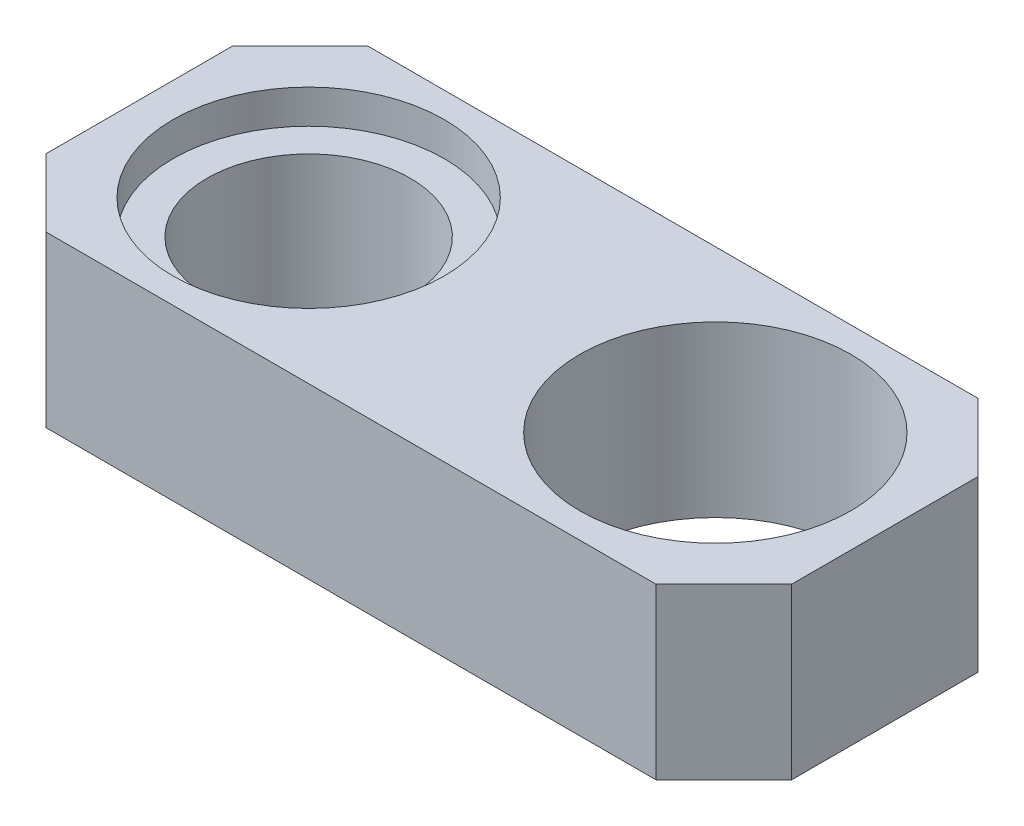
SolidWorks part; units mm, degrees
ref_plane "前视基准面" through (0, 0, 0) normal (0, 0, 1) x (1, 0, 0)
ref_plane "上视基准面" through (0, 0, 0) normal (0, 1, 0) x (1, 0, 0)
ref_plane "右视基准面" through (0, 0, 0) normal (1, 0, 0) x (0, 0, -1)
sketch "草图1" plane through (0, 0, 0) normal (0, 1, 0) x (1, 0, 0)
  line L1 (11, -4.75) -> (-11, -4.75)
  line L2 (11, -4.75) -> (11, 4.75)
  line L3 (11, 4.75) -> (-11, 4.75)
  line L4 (-11, -4.75) -> (-11, 4.75)
  line L5 (11, -4.75) -> (-11, 4.75) construction
  line L6 (11, 4.75) -> (-11, -4.75) construction
  point P0 (0, 0)
  dimension "D1" = 9.5
  dimension "D2" = 22
extrude "凸台-拉伸1" add sketch "草图1" along normal mid plane 5
sketch "草图2" plane through (0, 2.5, 0) normal (0, 1, 0) x (1, 0, 0)
  line L0 (0, 0) -> (0, 50000) construction
  line L1 (11, 4.75) -> (-11, 4.75) construction
  circle A0 centre (6, 0) radius 4
  point P5 (0, 4.75)
  dimension "D1" = 12
  dimension "D2" = 8
extrude "切除-拉伸1" cut sketch "草图2" against normal through all
sketch "草图3" plane through (0, 2.5, 0) normal (0, 1, 0) x (1, 0, 0)
  circle A0 centre (-6, 0) radius 4
  dimension "D1" = 8
  dimension "D2" = 6
extrude "切除-拉伸2" cut sketch "草图3" against normal blind 1
sketch "草图4" plane through (0, 1.5, 0) normal (0, 1, 0) x (1, 0, 0)
  circle A0 centre (-6, 0) radius 3
  circle A1 centre (-6, 0) radius 4 construction
  dimension "D1" = 6
extrude "切除-拉伸3" cut sketch "草图4" against normal through all
chamfer "倒角1" distance 2 angle 45 4 edges at (-11, 0, -4.75) (-11, 0, 4.75) (11, 0, 4.75) (11, 0, -4.75)
